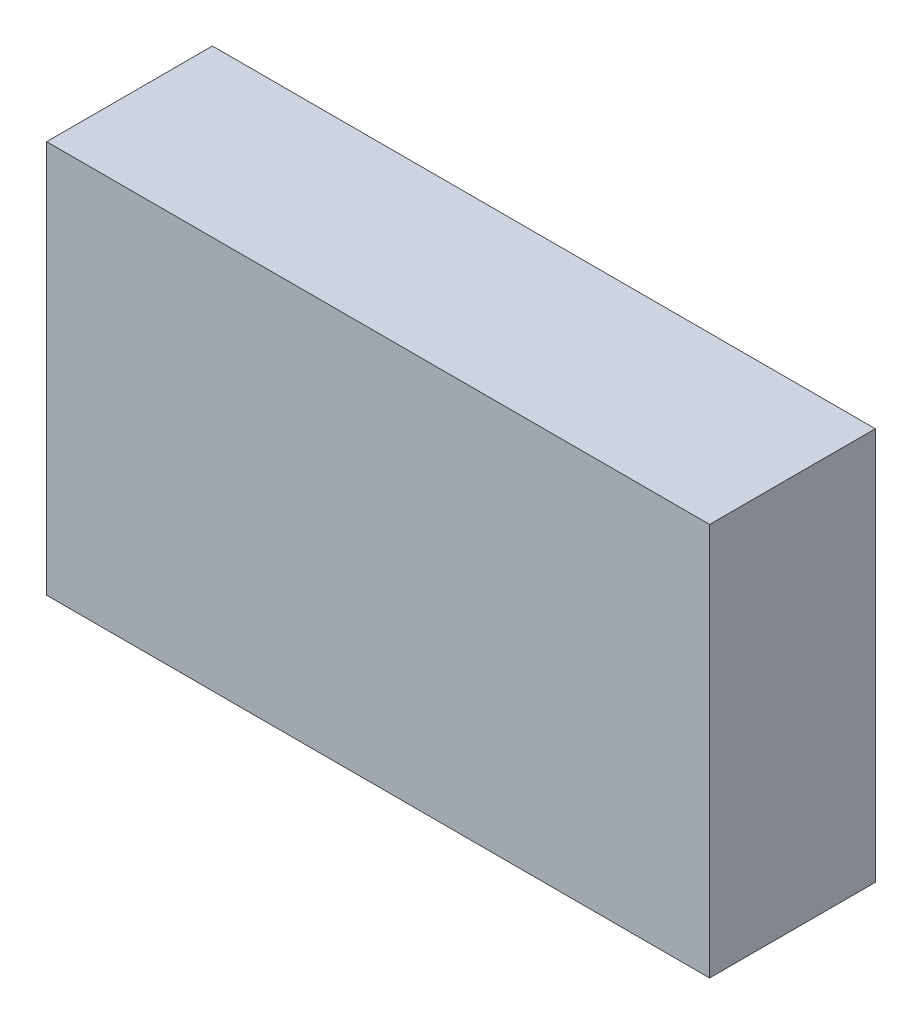
SolidWorks part; units mm, degrees
ref_plane "Front Plane" through (0, 0, 0) normal (0, 0, 1) x (1, 0, 0)
ref_plane "Top Plane" through (0, 0, 0) normal (0, 1, 0) x (1, 0, 0)
ref_plane "Right Plane" through (0, 0, 0) normal (1, 0, 0) x (0, 0, -1)
sketch "Sketch1" plane through (0, 0, 0) normal (0, 0, 1) x (1, 0, 0)
  line L1 (0, 0) -> (40, 0)
  line L2 (0, 0) -> (0, 23.7)
  line L3 (0, 23.7) -> (40, 23.7)
  line L4 (40, 0) -> (40, 23.7)
extrude "Boss-Extrude1" add sketch "Sketch1" against normal blind 10
